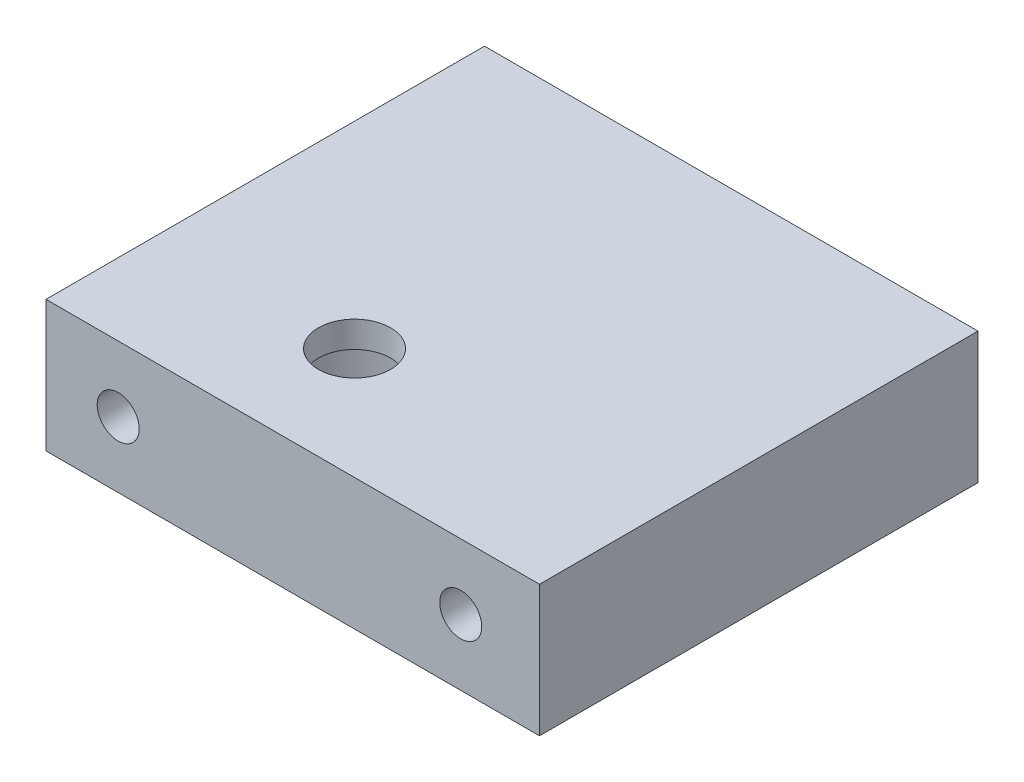
SolidWorks part; units mm, degrees
ref_plane "Front Plane" through (0, 0, 0) normal (0, 0, 1) x (1, 0, 0)
ref_plane "Top Plane" through (0, 0, 0) normal (0, 1, 0) x (1, 0, 0)
ref_plane "Right Plane" through (0, 0, 0) normal (1, 0, 0) x (0, 0, -1)
sketch "Sketch1" plane through (0, 0, 0) normal (0, 0, 1) x (1, 0, 0)
  line L1 (-8.7886, 15.5842) -> (28.8006, 15.5842)
  line L2 (-8.7886, 15.5842) -> (-8.7886, 5.5842)
  line L3 (-8.7886, 5.5842) -> (28.8006, 5.5842)
  line L4 (28.8006, 15.5842) -> (28.8006, 5.5842)
  line L5 (-8.7886, 15.5842) -> (28.8006, 5.5842) construction
  line L6 (-8.7886, 5.5842) -> (28.8006, 15.5842) construction
  point P0 (10.006, 10.5842)
  dimension "D1" = 10
  dimension "D2" = 37.5893
extrude "Boss-Extrude1" add sketch "Sketch1" along normal blind 33.4 contours L3 L4 L1 L2
sketch "Sketch2" plane through (0, 15.5842, 0) normal (0, 1, 0) x (1, 0, 0)
  line L0 (-8.7886, -33.4) -> (28.8006, -33.4) construction
  line L1 (-8.7886, -33.4) -> (-8.7886, 0) construction
  circle A0 centre (6.2114, -24.9) radius 6.5
  dimension "D1" = 13
  dimension "D2" = 8.5
  dimension "D3" = 15
extrude "Cut-Extrude1" cut sketch "Sketch2" against normal blind 10
sketch "Sketch3" plane through (0, 0, 33.4) normal (0, 0, 1) x (1, 0, 0)
  line L0 (-8.7886, 15.5842) -> (28.8006, 15.5842) construction
  line L1 (-8.7886, 15.5842) -> (-8.7886, 5.5842) construction
  line L2 (28.8006, 15.5842) -> (28.8006, 5.5842) construction
  circle A0 centre (-3.2886, 10.5842) radius 1.6
  circle A1 centre (22.8006, 10.5842) radius 1.6
  dimension "D1" = 3.2
  dimension "D4" = 3.2
  dimension "D2" = 5
  dimension "D3" = 5.5
  dimension "D5" = 6
  dimension "D6" = 5
extrude "Cut-Extrude2" cut sketch "Sketch3" against normal blind 50
sketch "Sketch4" plane through (0, 5.5842, 0) normal (0, -1, 0) x (1, 0, 0)
  circle A0 centre (6.2114, 24.9) radius 6.6
  circle A1 centre (6.2114, 24.9) radius 2.75
  dimension "D1" = 5.5
  dimension "D2" = 13.2
extrude "Boss-Extrude2" add sketch "Sketch4" against normal blind 2
mirror "Mirror1" about plane through (-8.7886, 15.5842, 33.4) normal (0, 1, 0) of bodies 105
delete or keep bodies "-1" type delete bodies bodies 105
